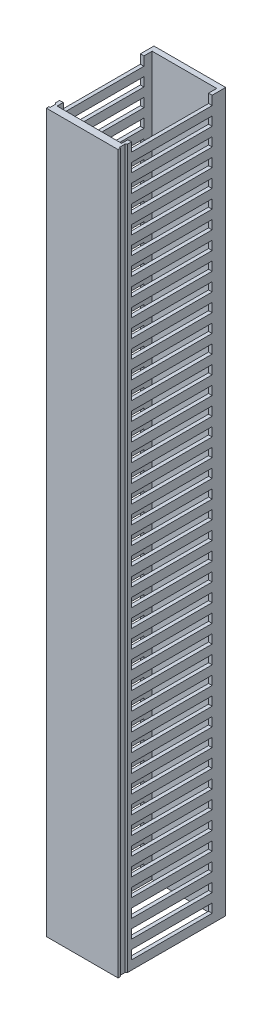
SolidWorks part; units mm, degrees
ref_plane "Front" through (0, 0, 0) normal (0, 0, 1) x (1, 0, 0)
ref_plane "Top" through (0, 0, 0) normal (0, 1, 0) x (1, 0, 0)
ref_plane "Right" through (0, 0, 0) normal (1, 0, 0) x (0, 0, -1)
sketch "Sketch1" plane through (0, 0, 0) normal (0, 1, 0) x (1, 0, 0)
  line L1 (0, 0) -> (40, 0)
  line L2 (0, 0) -> (0, 60)
  line L3 (0, 60) -> (40, 60)
  line L4 (40, 0) -> (40, 60)
extrude "Boss-Extrude1" add sketch "Sketch1" along normal blind 400
sketch "Sketch2" plane through (0, 0, 0) normal (0, -1, 0) x (1, 0, 0)
  line L0 (-1.6841, -1.4562) -> (0.6978, -1.4562)
  line L1 (0.6978, -1.4562) -> (0.6978, -4.5643)
  line L2 (0.6978, -4.5643) -> (-2.0327, -6.772)
  line L3 (-2.0327, -6.772) -> (-1.6841, -1.4562)
  line L4 (20, 0) -> (20, 4.9054) construction
  line L5 (0, 0) -> (40, 0) construction
  line L6 (42.0327, -6.772) -> (41.6841, -1.4562)
  line L7 (39.3022, -4.5643) -> (42.0327, -6.772)
  line L8 (39.3022, -1.4562) -> (39.3022, -4.5643)
  line L9 (41.6841, -1.4562) -> (39.3022, -1.4562)
extrude "Cut-Extrude1" cut sketch "Sketch2" against normal through all
sketch "Sketch3" plane through (0, 0, 0) normal (-1, 0, 0) x (0, 0, 1)
  line L0 (-60, 0) -> (-5.1285, 0) construction
  line L1 (-7.4463, 10) -> (-52.4463, 10)
  line L2 (-7.4463, 10) -> (-7.4463, 5)
  line L3 (-7.4463, 5) -> (-52.4463, 5)
  line L4 (-52.4463, 10) -> (-52.4463, 5)
  dimension "D1" = 5
  dimension "D2" = 45
  dimension "D3" = 5
extrude "Cut-Extrude2" cut sketch "Sketch3" against normal through all
sketch "Sketch4" plane through (0, 400, 0) normal (0, 1, 0) x (1, 0, 0)
  line L0 (40, 5.1285) -> (40, 60) construction
  line L1 (38, 4) -> (2, 4)
  line L2 (38, 4) -> (38, 57)
  line L3 (38, 57) -> (2, 57)
  line L4 (2, 4) -> (2, 57)
  line L5 (0, 60) -> (0, 5.1285) construction
  line L6 (0, 0) -> (40, 0) construction
  line L7 (40, 60) -> (0, 60) construction
  dimension "D1" = 2
  dimension "D2" = 2
  dimension "D3" = 4
  dimension "D4" = 3
extrude "Cut-Extrude3" cut sketch "Sketch4" against normal through all
pattern_linear "LPattern1" count 40 spacing 10 along (0, 1, 0) of "Cut-Extrude2"
